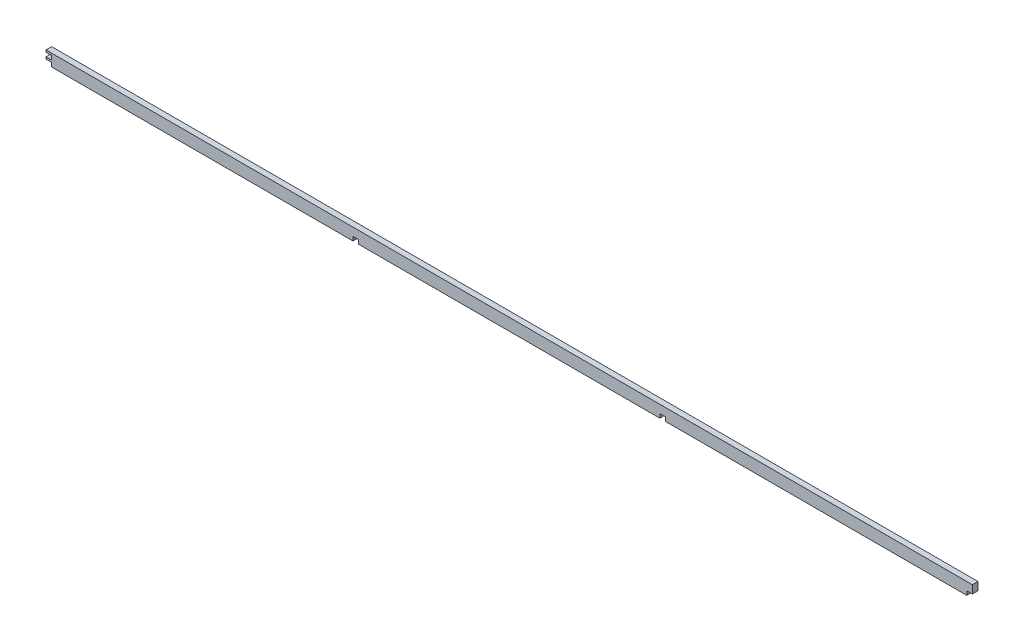
SolidWorks part; units mm, degrees
material "Фанера"
ref_plane "Front Plane" through (0, 0, 0) normal (0, 0, 1) x (1, 0, 0)
ref_plane "Top Plane" through (0, 0, 0) normal (0, 1, 0) x (1, 0, 0)
ref_plane "Right Plane" through (0, 0, 0) normal (1, 0, 0) x (0, 0, -1)
sketch "Эскиз2" plane through (0, 0, 0) normal (0, 0, 1) x (1, 0, 0)
  line L0 (-79.2, 16.0584) -> (-79.2, -22.9321) construction
  line L1 (-229.2, -3) -> (-79.2, -3)
  line L2 (-229.2, -3) -> (-229.2, -1)
  line L3 (-229.2, 3) -> (229.2, 3)
  line L4 (229.2, -1) -> (229.2, 3)
  line L5 (-229.2, -3) -> (229.2, 3) construction
  line L6 (-229.2, 3) -> (226.4, -2.9634) construction
  line L7 (-229.2, 2) -> (-232, 2)
  line L10 (-232, 2) -> (-232, 3)
  line L11 (-76.4, 12.1277) -> (-76.4, -19.9797) construction
  line L12 (-232, 3) -> (-229.2, 3)
  line L13 (-233.0787, 1) -> (-225.558, 1) construction
  line L14 (-232, -1) -> (-229.2, -1)
  line L15 (-229.2, 0) -> (-232, 0)
  line L16 (-232, 0) -> (-232, -1)
  line L17 (-229.2, 0) -> (-229.2, 2)
  line L18 (73.6, 14.8857) -> (73.6, -40.87) construction
  line L19 (76.4, 14.8857) -> (76.4, -40.87) construction
  line L20 (-79.2, -3) -> (-79.2, -1)
  line L21 (-79.2, -1) -> (-76.4, -1)
  line L22 (-76.4, -1) -> (-76.4, -3)
  line L23 (-76.4, -3) -> (73.6, -3)
  line L24 (73.6, -3) -> (73.6, -1)
  line L25 (73.6, -1) -> (76.4, -1)
  line L26 (76.4, -1) -> (76.4, -3)
  line L27 (76.4, -3) -> (226.4, -3)
  line L28 (226.4, -3) -> (226.4, -1)
  line L29 (226.4, -1) -> (229.2, -1)
  point P0 (0, 0)
  dimension "D1" = 458.4
  dimension "D2" = 6
  dimension "D3" = 1
  dimension "D4" = 2.8
  dimension "D5" = 2
  dimension "D6" = 150
  dimension "D7" = 2.8
  dimension "D8" = 150
  dimension "D9" = 2.8
  dimension "D10" = 4
  dimension "D11" = 4
  dimension "D12" = 4
  dimension "D13" = 2.8
extrude "Бобышка-Вытянуть1" add sketch "Эскиз2" along normal mid plane 2.8
